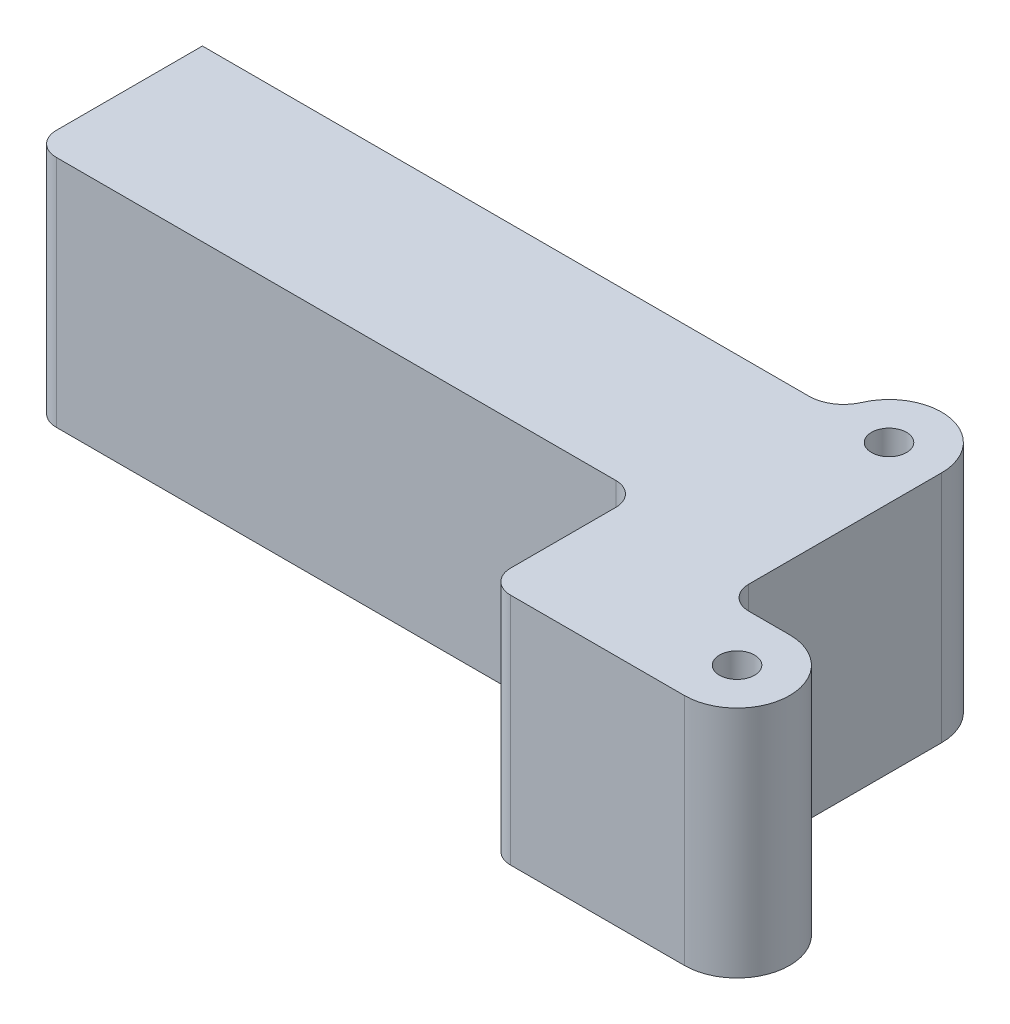
SolidWorks part; units mm, degrees
ref_plane "Front Plane" through (0, 0, 0) normal (0, 0, 1) x (1, 0, 0)
ref_plane "Top Plane" through (0, 0, 0) normal (0, 1, 0) x (1, 0, 0)
ref_plane "Right Plane" through (0, 0, 0) normal (1, 0, 0) x (0, 0, -1)
sketch "Sketch1" plane through (0, 0, 0) normal (0, 0, 1) x (1, 0, 0)
  line L1 (-36.7213, 7.7049) -> (33.2787, 7.7049)
  line L2 (-36.7213, 7.7049) -> (-36.7213, -12.2951)
  line L3 (-36.7213, -12.2951) -> (33.2787, -12.2951)
  line L4 (33.2787, 7.7049) -> (33.2787, -12.2951)
  dimension "D1" = 70
  dimension "D2" = 20
extrude "Boss-Extrude1" add sketch "Sketch1" along normal blind 5
sketch "Sketch3" plane through (0, 7.7049, 0) normal (0, 1, 0) x (1, 0, 0)
  line L1 (33.2787, 0) -> (24.2787, 0)
  line L2 (33.2787, 0) -> (33.2787, 9.5)
  line L3 (33.2787, 9.5) -> (24.2787, 9.5)
  line L4 (24.2787, 0) -> (24.2787, 9.5)
  circle A0 centre (28.7787, 9.5) radius 4.5
  circle A1 centre (28.7787, 9.5) radius 1.5
  line M6 (33.2787, 0) -> (-36.7213, 0)
  dimension "D3" = 3
  dimension "D1" = 9
  dimension "D2" = 9.5
extrude "Boss-Extrude3" add sketch "Sketch3" against normal blind 20 contours A1 L3 A0 | A1 L3 A0 | A0 L4 L2 M6
fillet "Fillet1" radius 5 1 edges at (24.2787, -2.2951, 0)
sketch "Sketch4" plane through (0, 7.7049, 0) normal (0, 1, 0) x (1, 0, 0)
  line L1 (33.2787, -5) -> (41.2787, -5)
  line L2 (33.2787, -5) -> (33.2787, 0)
  line L3 (33.2787, 0) -> (41.2787, 0)
  line L4 (41.2787, -5) -> (41.2787, 0)
  line L5 (41.2787, -5) -> (32.2787, -5)
  line L6 (41.2787, -5) -> (41.2787, -14)
  line L7 (41.2787, -14) -> (32.2787, -14)
  line L8 (32.2787, -5) -> (32.2787, -14)
  circle A0 centre (36.7787, -14) radius 4.5
  circle A1 centre (36.7787, -14) radius 1.5
  circle A2 centre (28.7787, 9.5) radius 1.5
  line M10 (-36.7213, -5) -> (33.2787, -5)
  dimension "D4" = 3
  dimension "D1" = 8
  dimension "D2" = 9
  dimension "D3" = 9
extrude "Boss-Extrude4" add sketch "Sketch4" against normal blind 20 contours A0 L6 L1 L8 M10 | A1 L7 A0 | A1 L7 A0
fillet "Fillet2" radius 5 1 edges at (32.2787, -2.2951, 5)
fillet "Fillet3" radius 5 1 edges at (33.2787, -2.2951, 0)
fillet "Fillet4" radius 5 1 edges at (41.2787, -2.2951, 0)
sketch "Sketch5" plane through (0, 0, 0) normal (0, 0, -1) x (-1, 0, 0)
  line L0 (-19.2787, 7.7049) -> (-19.2787, -12.2951) construction
  line L1 (36.7213, 7.7049) -> (-19.2787, 7.7049)
  line L2 (36.7213, 7.7049) -> (36.7213, -12.2951)
  line L3 (36.7213, -12.2951) -> (-19.2787, -12.2951)
  line L4 (-19.2787, 7.7049) -> (-19.2787, -12.2951)
  dimension "D1" = 20
extrude "Boss-Extrude5" add sketch "Sketch5" along normal blind 5
sketch "Sketch6" plane through (0, 7.7049, 0) normal (0, 1, 0) x (1, 0, 0)
  line L0 (19.2787, 0) -> (-36.7213, 0)
  line L1 (-36.7213, -5) -> (-36.7213, 5) construction
  line L2 (19.2787, 0) -> (14.2787, 5)
  line L3 (-36.7213, 5) -> (19.2787, 5) construction
  line L4 (14.2787, 5) -> (9.2787, 0)
  line L5 (9.2787, 0) -> (4.2787, 5)
  line L6 (4.2787, 5) -> (-0.7213, 0)
  line L7 (-0.7213, 0) -> (-5.7213, 5)
  line L8 (-5.7213, 5) -> (-10.7213, 0)
  line L9 (-10.7213, 0) -> (-15.7213, 5)
  line L10 (-15.7213, 5) -> (-20.7213, 0)
  line L11 (-20.7213, 0) -> (-25.7213, 5)
  line L12 (-25.7213, 5) -> (-30.7213, 0)
  line L13 (-30.7213, 0) -> (-35.7213, 5)
  line L14 (-35.7213, 5) -> (-40.7213, 0)
  line L15 (-40.7213, 0) -> (-40.7213, 5)
  line L16 (-40.7213, 5) -> (19.2787, 5)
  line L17 (19.2787, 5) -> (19.2787, 0)
  line L19 (-36.7213, -5) -> (-40.7213, -5)
  line L20 (-36.7213, -5) -> (-36.7213, 5)
  line L21 (-36.7213, 5) -> (-40.7213, 5)
  line L22 (-40.7213, -5) -> (-40.7213, 5)
extrude "Cut-Extrude2" cut sketch "Sketch6" against normal blind 20 contours L13 L12 L8 | L11 L10 L8 | L7 L6 L8 | L9 L8 | L5 L4 L8 | L2 L7 L8 | L14 L8 L9 | L16 L15 L14 L9
fillet "Fillet5" radius 2 12 edges at (19.2787, -2.2951, 0) (14.2787, -2.2951, -5) (9.2787, -2.2951, 0) (4.2787, -2.2951, -5) (-0.7213, -2.2951, 0) (-5.7213, -2.2951, -5) (-10.7213, -2.2951, 0) (-15.7213, -2.2951, -5) (-20.7213, -2.2951, 0) (-25.7213, -2.2951, -5) (-30.7213, -2.2951, 0) (-35.7213, -2.2951, -5)
sketch "Sketch9" plane through (0, 7.7049, 0) normal (0, 1, 0) x (1, 0, 0)
  line L0 (27.2787, -5) -> (-36.7213, -5) construction
  line L1 (-30.7213, -5) -> (-36.7213, -5)
  line L2 (-30.7213, -5) -> (-30.7213, 4.5189)
  line L3 (-30.7213, 4.5189) -> (-36.7213, 4.5189)
  line L4 (-36.7213, -5) -> (-36.7213, 4.5189)
extrude "Cut-Extrude3" cut sketch "Sketch9" against normal blind 20
sketch "Sketch11" plane through (0, 7.7049, 0) normal (0, 1, 0) x (1, 0, 0)
  line L1 (-30.7213, -5) -> (-40.1291, -5)
  line L2 (-30.7213, -5) -> (-30.7213, 5.8216)
  line L3 (-30.7213, 5.8216) -> (-40.1291, 5.8216)
  line L4 (-40.1291, -5) -> (-40.1291, 5.8216)
sketch "Sketch12" plane through (0, 7.7049, 0) normal (0, 1, 0) x (1, 0, 0)
  line L1 (-29.9559, 0.9807) -> (-30.7213, 0.9807)
  line L2 (-29.9559, 0.9807) -> (-29.9559, -5)
  line L3 (-29.9559, -5) -> (-30.7213, -5)
  line L4 (-30.7213, 0.9807) -> (-30.7213, -5)
  arc A0 (-30.7213, 0.8284) -> (-29.3071, 1.4142) centre (-30.7213, 2.8284) ccw construction
extrude "Cut-Extrude5" cut sketch "Sketch12" against normal blind 20
fillet "Fillet7" radius 1 1 edges at (-29.9559, -2.2951, -0.9807)
sketch "Sketch13" plane through (0, 7.7049, 0) normal (0, 1, 0) x (1, 0, 0)
  line L0 (33.2787, 5) -> (42.1777, 4.101)
  line L1 (42.1777, 4.101) -> (41.2787, -4.798)
  arc A0 (33.2787, 5) -> (41.2787, -4.798) centre (42.1777, 4.101) ccw
extrude "Cut-Extrude6" cut sketch "Sketch13" against normal through all
fillet "Fillet8" radius 10 1 edges at (41.2787, -2.2951, 4.798)
sketch "Sketch14" plane through (0, 7.7049, 0) normal (0, 1, 0) x (1, 0, 0)
  line L1 (-29.9559, 0.4028) -> (24.2787, 0.4028)
  line L2 (-29.9559, 0.4028) -> (-29.9559, 9.5)
  line L3 (-29.9559, 9.5) -> (24.2787, 9.5)
  line L4 (24.2787, 0.4028) -> (24.2787, 9.5)
extrude "Boss-Extrude6" add sketch "Sketch14" against normal through all
sketch "Sketch15" plane through (0, 7.7049, 0) normal (0, 1, 0) x (1, 0, 0)
  circle A0 centre (17.358, 0) radius 4.7018
extrude "Boss-Extrude7" add sketch "Sketch15" against normal through all
fillet "Fillet9" radius 3 1 edges at (24.2787, -2.2951, -9.5)
sketch "Sketch16" plane through (0, 7.7049, 0) normal (0, 1, 0) x (1, 0, 0)
  line L0 (27.2787, -5) -> (32.2787, -5)
  line L1 (32.2787, -5) -> (32.2787, -10)
  arc A0 (27.2787, -5) -> (32.2787, -10) centre (32.2787, -5) ccw
extrude "Boss-Extrude8" add sketch "Sketch16" against normal through all
fillet "Fillet10" [suppressed] radius 12
fillet "Fillet11" radius 2 2 edges at (-29.9559, -2.2951, 5) (-29.9559, -2.2951, -9.5)
sketch "Sketch17" plane through (0, 7.7049, 0) normal (0, 1, 0) x (1, 0, 0)
  line L1 (33.2787, 5) -> (21.9048, 5)
  line L2 (33.2787, 5) -> (33.2787, -18.4851)
  line L3 (33.2787, -18.4851) -> (21.9048, -18.4851)
  line L4 (21.9048, 5) -> (21.9048, -18.4851)
extrude "Boss-Extrude9" add sketch "Sketch17" against normal through all
sketch "Sketch18" plane through (0, 7.7049, 0) normal (0, 1, 0) x (1, 0, 0)
  line L0 (21.9048, -5) -> (21.9048, -18.4851) construction
  line L1 (36.7787, -18.5) -> (21.9048, -18.5)
  line L2 (36.7787, -18.5) -> (36.7787, -16.2712)
  line L3 (36.7787, -16.2712) -> (21.9048, -16.2712)
  line L4 (21.9048, -18.5) -> (21.9048, -16.2712)
  arc A0 (33.2787, -16.8284) -> (41.2787, -14) centre (36.7787, -14) ccw construction
extrude "Boss-Extrude10" add sketch "Sketch18" against normal through all
sketch "Sketch19" plane through (0, 7.7049, 0) normal (0, 1, 0) x (1, 0, 0)
  line L0 (41.2787, -14) -> (41.0977, -9.5)
  line L5 (33.2787, 3.202) -> (41.0977, 3.202)
  line L6 (33.2787, 3.202) -> (33.2787, -9.5)
  line L7 (33.2787, -9.5) -> (41.0977, -9.5)
  line L8 (41.0977, 3.202) -> (41.0977, -9.5)
  circle A0 centre (36.7787, -14) radius 4.5
  arc A1 (41.2787, -11.3941) -> (37.0319, -3.2148) centre (31.2787, -11.3941) ccw construction
  arc A2 (36.7787, -9.5) -> (41.2787, -14) centre (36.7787, -14) cw
extrude "Cut-Extrude7" cut sketch "Sketch19" against normal through all
sketch "Sketch20" plane through (0, 7.7049, 0) normal (0, 1, 0) x (1, 0, 0)
  line L0 (36.7787, -9.5) -> (44.0075, -9.5)
  line L1 (44.0075, -9.5) -> (44.0075, -18.5)
  line L2 (44.0075, -18.5) -> (36.7787, -18.5)
  arc A0 (36.7787, -9.5) -> (41.2787, -14) centre (36.7787, -14) cw
  arc A1 (41.2787, -14) -> (36.7787, -18.5) centre (36.7787, -14) cw
extrude "Cut-Extrude8" cut sketch "Sketch20" against normal through all
fillet "Fillet12" radius 2 2 edges at (21.9048, -2.2951, 5) (33.2787, -2.2951, 9.5)
fillet "Fillet13" radius 2 1 edges at (21.9048, -2.2951, 18.5)
sketch "Sketch21" plane through (0, 7.7049, 0) normal (0, 1, 0) x (1, 0, 0)
  line L1 (19.9048, -5) -> (44.5148, -5)
  line L2 (19.9048, -5) -> (19.9048, -19.223)
  line L3 (19.9048, -19.223) -> (44.5148, -19.223)
  line L4 (44.5148, -5) -> (44.5148, -19.223)
  circle A0 centre (28.7787, 9.5) radius 1.5
  circle A1 centre (36.7787, -14) radius 1.5
  dimension "D1" = 8
  dimension "D2" = 23.5
extrude "Cut-Extrude10" cut sketch "Sketch21" against normal through all
sketch "Sketch24" plane through (0, 7.7049, 0) normal (0, 1, 0) x (1, 0, 0)
  line L0 (33.2787, -5) -> (45.257, -5)
  line L1 (33.2787, -5) -> (33.2787, 9.5) construction
  line L2 (34.2787, -13.5) -> (43.2787, -13.5)
  line L3 (34.2787, -13.5) -> (34.2787, -5)
  line L4 (34.2787, -5) -> (43.2787, -5)
  line L5 (43.2787, -13.5) -> (43.2787, -5)
  line L6 (43.2787, -5) -> (33.2787, -5)
  line L7 (43.2787, -5) -> (43.2787, 2.25)
  line L8 (43.2787, 2.25) -> (33.2787, 2.25)
  line L9 (33.2787, -5) -> (33.2787, 2.25)
  circle A0 centre (28.7787, 9.5) radius 1.5
  circle A1 centre (38.7787, -13.5) radius 1.5
  circle A2 centre (38.7787, -13.5) radius 4.5
  line M4 (33.2787, -5) -> (33.2787, 9.5)
  dimension "D1" = 3
  dimension "D2" = 9
  dimension "D3" = 10
  dimension "D4" = 23
extrude "Boss-Extrude11" add sketch "Sketch24" against normal blind 20 contours L7 L8 L0 M4 | A2 L5 L0 L3 | L2 A2 A1 | L2 A2 A1
fillet "Fillet14" radius 2 2 edges at (33.2787, -2.2951, -2.25) (34.2787, -2.2951, 5)
fillet "Fillet15" radius 10 1 edges at (43.2787, -2.2951, -2.25)
sketch "Sketch25" plane through (0, 7.7049, 0) normal (0, 1, 0) x (1, 0, 0)
  line L0 (38.7787, -18) -> (13.7787, -18)
  line L1 (38.7787, -18) -> (34.2787, -18)
  line L2 (13.7787, -18) -> (34.2787, -18)
  line L3 (13.7787, -18) -> (13.7787, -5)
  line L4 (13.7787, -5) -> (34.2787, -5)
  line L5 (34.2787, -18) -> (34.2787, -5)
  arc A0 (34.2787, -13.5) -> (43.2787, -13.5) centre (38.7787, -13.5) ccw construction
  arc A1 (38.7787, -18) -> (34.2787, -13.5) centre (38.7787, -13.5) cw
  line M16 (-27.9559, -5) -> (32.2787, -5)
  arc M17 (32.2787, -5) -> (34.2787, -7) centre (32.2787, -7) cw
  line M18 (34.2787, -7) -> (34.2787, -13.5)
  arc M19 (34.2787, -13.5) -> (43.2787, -13.5) centre (38.7787, -13.5) ccw
  dimension "D1" = 25
extrude "Boss-Extrude12" add sketch "Sketch25" against normal through all contours L0 L5 L3 M18 M17 M16 | L5 L0 M19
sketch "Sketch26" plane through (0, 7.7049, 0) normal (0, 1, 0) x (1, 0, 0)
  line L1 (33.2787, 4.25) -> (43.2787, 4.25)
  line L2 (33.2787, 4.25) -> (33.2787, -7.5822)
  line L3 (33.2787, -7.5822) -> (43.2787, -7.5822)
  line L4 (43.2787, 4.25) -> (43.2787, -7.5822)
extrude "Cut-Extrude11" cut sketch "Sketch26" against normal through all
sketch "Sketch27" plane through (0, 7.7049, 0) normal (0, 1, 0) x (1, 0, 0)
  line L0 (38.7787, -9) -> (33.2787, -9)
  line L1 (33.2787, -7.5822) -> (33.2787, -9)
  line L2 (43.2787, -13.5) -> (43.2787, -7.5822)
  line L3 (43.2787, -7.5822) -> (33.2787, -7.5822)
  circle A0 centre (38.7787, -13.5) radius 4.5
  arc A1 (38.7787, -9) -> (43.2787, -13.5) centre (38.7787, -13.5) cw
  line M2 (43.2787, -7.5822) -> (33.2787, -7.5822)
  line M14 (43.2787, -13.5) -> (43.2787, -7.5822)
extrude "Cut-Extrude12" cut sketch "Sketch27" against normal through all contours A0 L1 L0 M14 M2
sketch "Sketch28" plane through (0, 7.7049, 0) normal (0, 1, 0) x (1, 0, 0)
  line L0 (21.9048, 9.5) -> (21.9048, -18)
  line L1 (38.7787, -18) -> (13.7787, -18) construction
  line L3 (13.7787, -5) -> (21.9048, -5)
  line L4 (13.7787, -5) -> (13.7787, -18)
  line L5 (13.7787, -18) -> (21.9048, -18)
  line L6 (21.9048, -5) -> (21.9048, -18)
  line M13 (13.7787, -5) -> (13.7787, -18)
  line M14 (13.7787, -18) -> (38.7787, -18)
extrude "Cut-Extrude13" cut sketch "Sketch28" against normal through all contours L3 L0 M13 M14
fillet "Fillet16" radius 2 3 edges at (33.2787, -2.2951, 9) (21.9048, -2.2951, 18) (21.9048, -2.2951, 5)
sketch "Sketch29" plane through (0, 7.7049, 0) normal (0, 1, 0) x (1, 0, 0)
  line L1 (-29.9559, 7.5) -> (-27.9559, 7.5)
  line L2 (-29.9559, 7.5) -> (-29.9559, 9.5)
  line L3 (-29.9559, 9.5) -> (-27.9559, 9.5)
  line L4 (-27.9559, 7.5) -> (-27.9559, 9.5)
extrude "Boss-Extrude13" add sketch "Sketch29" against normal through all
